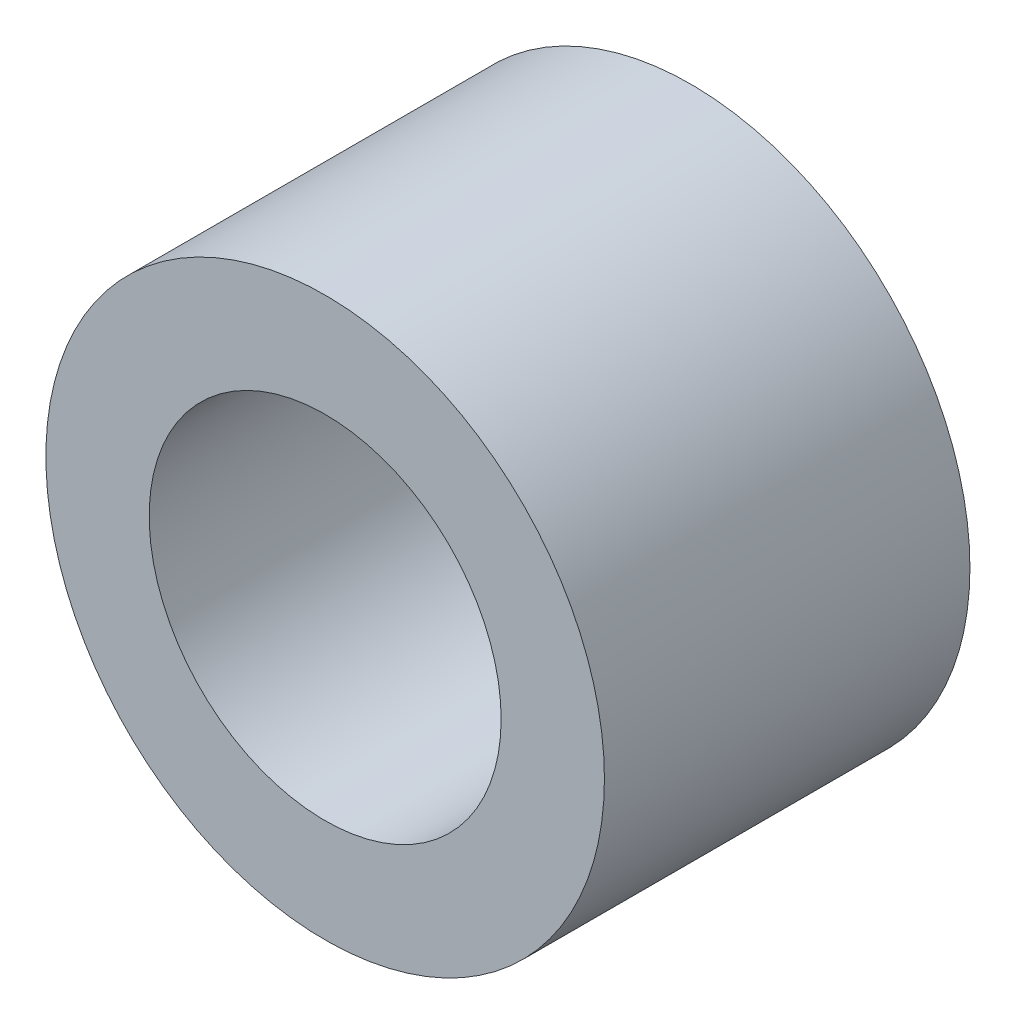
SolidWorks part; units mm, degrees
ref_plane "Piano frontale" through (0, 0, 0) normal (0, 0, 1) x (1, 0, 0)
ref_plane "Piano superiore" through (0, 0, 0) normal (0, 1, 0) x (1, 0, 0)
ref_plane "Piano destro" through (0, 0, 0) normal (1, 0, 0) x (0, 0, -1)
sketch "Schizzo1" plane through (0, 0, 0) normal (0, 0, 1) x (1, 0, 0)
  circle A0 centre (0, 0) radius 2.99
  circle A1 centre (0, 0) radius 4.745
  dimension "D1" = 5.98
  dimension "D2" = 9.49
extrude "Estrusione-Estrusione1" add sketch "Schizzo1" along normal blind 6.21
